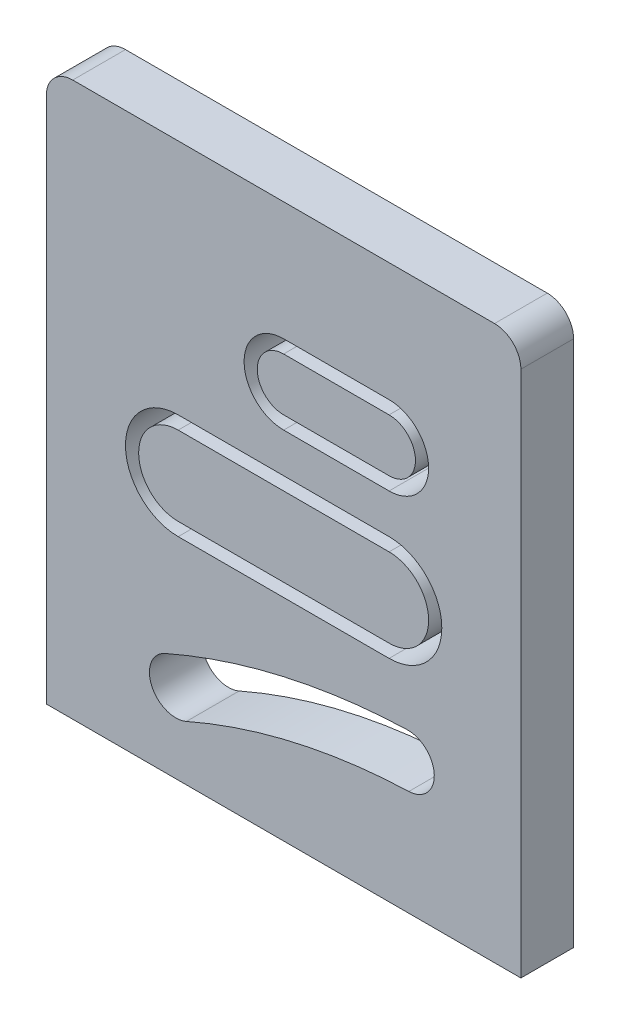
SolidWorks part; units mm, degrees
ref_plane "Front Plane" through (0, 0, 0) normal (0, 0, 1) x (1, 0, 0)
ref_plane "Top Plane" through (0, 0, 0) normal (0, 1, 0) x (1, 0, 0)
ref_plane "Right Plane" through (0, 0, 0) normal (1, 0, 0) x (0, 0, -1)
sketch "草图1" plane through (0, 0, 0) normal (0, 0, 1) x (1, 0, 0)
  line L0 (-399.0643, 166.2102) -> (-399.0643, -43.7898) construction
  line L1 (-479.0643, 166.2102) -> (-319.0643, 166.2102)
  line L2 (-489.0643, 156.2102) -> (-489.0643, -43.7898)
  line L3 (-489.0643, -43.7898) -> (-309.0643, -43.7898)
  line L4 (-309.0643, 156.2102) -> (-309.0643, -43.7898)
  line L5 (-489.0643, 166.2102) -> (-309.0643, -43.7898) construction
  line L6 (-489.0643, -43.7898) -> (-309.0643, 166.2102) construction
  line L13 (-399.0643, 106.2102) -> (-359.0643, 106.2102) construction
  line L18 (-399.0643, 121.2102) -> (-359.0643, 121.2102)
  line L19 (-399.0643, 91.2102) -> (-359.0643, 91.2102)
  line L20 (-439.0643, 56.2102) -> (-359.0643, 56.2102) construction
  line L23 (-439.0643, 76.2102) -> (-359.0643, 76.2102)
  line L24 (-439.0643, 36.2102) -> (-359.0643, 36.2102)
  line L25 (-399.0643, 116.2102) -> (-359.0643, 116.2102)
  line L26 (-399.0643, 96.2102) -> (-359.0643, 96.2102)
  line L27 (-439.0643, 71.2102) -> (-359.0643, 71.2102)
  line L28 (-439.0643, 41.2102) -> (-359.0643, 41.2102)
  arc A0 (-309.0643, 156.2102) -> (-319.0643, 166.2102) centre (-319.0643, 156.2102) ccw
  arc A1 (-479.0643, 166.2102) -> (-489.0643, 156.2102) centre (-479.0643, 156.2102) ccw
  arc A10 (-399.0643, 121.2102) -> (-399.0643, 91.2102) centre (-399.0643, 106.2102) ccw
  arc A11 (-359.0643, 91.2102) -> (-359.0643, 121.2102) centre (-359.0643, 106.2102) ccw
  arc A14 (-439.0643, 76.2102) -> (-439.0643, 36.2102) centre (-439.0643, 56.2102) ccw
  arc A15 (-359.0643, 36.2102) -> (-359.0643, 76.2102) centre (-359.0643, 56.2102) ccw
  arc A18 (-439.9743, -13.7898) -> (-351.9214, 6.2102) centre (-344.2455, -231.417) cw construction
  arc A23 (-352.2443, 16.205) -> (-444.0007, -4.6363) centre (-344.2455, -231.417) ccw
  arc A24 (-351.5986, -3.7846) -> (-435.9479, -22.9434) centre (-344.2455, -231.417) ccw
  arc A25 (-351.5986, -3.7846) -> (-352.2443, 16.205) centre (-351.9214, 6.2102) ccw
  arc A26 (-444.0007, -4.6363) -> (-435.9479, -22.9434) centre (-439.9743, -13.7898) ccw
  arc A27 (-359.0643, 96.2102) -> (-359.0643, 116.2102) centre (-359.0643, 106.2102) ccw
  arc A28 (-399.0643, 116.2102) -> (-399.0643, 96.2102) centre (-399.0643, 106.2102) ccw
  arc A29 (-359.0643, 41.2102) -> (-359.0643, 71.2102) centre (-359.0643, 56.2102) ccw
  arc A30 (-439.0643, 71.2102) -> (-439.0643, 41.2102) centre (-439.0643, 56.2102) ccw
  point P0 (-399.0643, 61.2102)
  point P15 (-379.0643, 106.2102)
  point P22 (-399.0643, 56.2102)
  point P30 (-396.906, 0.4288)
  point P35 (0, 0)
  point P36 (0, 0)
  point P37 (0, 0)
  point P38 (0, 0)
  point P39 (0, 0)
  point P40 (0, 0)
  point P41 (0, 0)
  point P42 (0, 0)
  point P43 (0, 0)
  point P44 (0, 0)
  point P45 (0, 0)
  point P46 (0, 0)
  point P47 (0, 0)
  point P48 (0, 0)
  point P49 (0, 0)
  point P50 (0, 0)
  dimension "D1" = 10
  dimension "D9" = 50
  dimension "D10" = 43.18
  dimension "D12" = 10
  dimension "D2" = 160
  dimension "D3" = 210
  dimension "D4" = 40
  dimension "D5" = 40
  dimension "D6" = 60
  dimension "D7" = 110
  dimension "D8" = 80
  dimension "D11" = 49.09
  dimension "D13" = 30
  dimension "D14" = 30
  dimension "D15" = 5
  dimension "D16" = 5
extrude "凸台-拉伸10" add sketch "草图1" along normal blind 20 contours L1 A1 L2 L3 L4 A0 A26 A23 A25 A24 A15 L24 A14 L23 A11 L19 A10 L18 | L25 A28 L26 A27 | L27 A30 L28 A29
